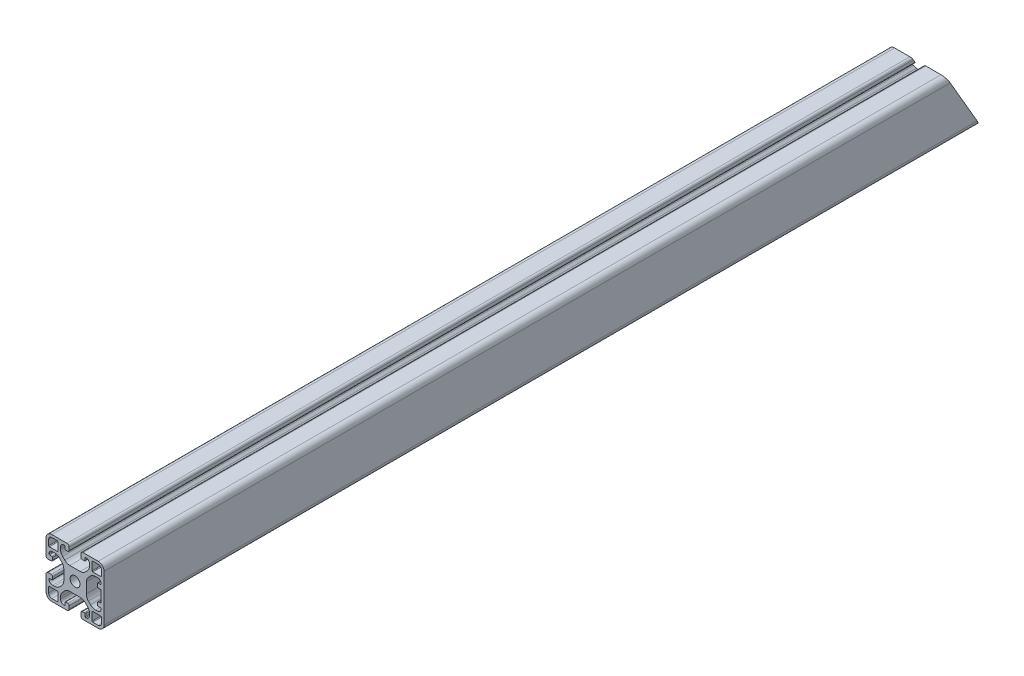
SolidWorks part; units mm, degrees
ref_plane "Piano frontale" through (0, 0, 0) normal (0, 0, 1) x (1, 0, 0)
ref_plane "Piano superiore" through (0, 0, 0) normal (0, 1, 0) x (1, 0, 0)
ref_plane "Piano destro" through (0, 0, 0) normal (1, 0, 0) x (0, 0, -1)
ref_plane "Piano1" through (0, 0, -340) normal (0, 0, -1) x (-1, 0, 0)
sketch "Schizzo1" plane through (0, 0, -340) normal (0, 0, -1) x (-1, 0, 0)
  line L0 (-12.3, -18.2) -> (-16, -18.2)
  line L1 (-18.2, -16) -> (-18.2, -12.3)
  line L2 (-17.7, -11.8) -> (-12.3, -11.8)
  line L3 (-11.8, -12.3) -> (-11.8, -17.7)
  line L4 (-11.8, 17.7) -> (-11.8, 12.3)
  line L5 (-12.3, 11.8) -> (-17.7, 11.8)
  line L6 (-18.2, 12.3) -> (-18.2, 16)
  line L7 (-16, 18.2) -> (-12.3, 18.2)
  line L8 (18.2, 16) -> (18.2, 12.3)
  line L9 (17.7, 11.8) -> (12.3, 11.8)
  line L10 (11.8, 12.3) -> (11.8, 17.7)
  line L11 (12.3, 18.2) -> (16, 18.2)
  line L12 (6.5, -15.5) -> (5, -15.5)
  line L13 (4, -16.5) -> (4, -18.5)
  line L14 (5.5, -20) -> (16, -20)
  line L15 (20, -16) -> (20, -5.5)
  line L16 (18.5, -4) -> (16.5, -4)
  line L17 (15.5, -5) -> (15.5, -6.5)
  line L18 (16, -7) -> (17.55, -7)
  line L19 (18, -7.45) -> (18, -7.5)
  line L20 (15.5, -10) -> (14.1924, -10)
  line L21 (10.6569, -8.5355) -> (9.2145, -7.0931)
  line L22 (7.75, -3.5576) -> (7.75, 3.5576)
  line L23 (9.2145, 7.0931) -> (10.6569, 8.5355)
  line L24 (14.1924, 10) -> (15.5, 10)
  line L25 (18, 7.5) -> (18, 7.45)
  line L26 (17.55, 7) -> (16, 7)
  line L27 (15.5, 6.5) -> (15.5, 5)
  line L28 (16.5, 4) -> (18.5, 4)
  line L29 (20, 5.5) -> (20, 16)
  line L30 (16, 20) -> (5.5, 20)
  line L31 (4, 18.5) -> (4, 16.5)
  line L32 (5, 15.5) -> (6.5, 15.5)
  line L33 (7, 16) -> (7, 17.55)
  line L34 (7.45, 18) -> (7.5, 18)
  line L35 (10, 15.5) -> (10, 14.1924)
  line L36 (8.5355, 10.6569) -> (7.0931, 9.2145)
  line L37 (3.5576, 7.75) -> (-3.5576, 7.75)
  line L38 (-7.0931, 9.2145) -> (-8.5355, 10.6569)
  line L39 (-10, 14.1924) -> (-10, 15.5)
  line L40 (-7.5, 18) -> (-7.45, 18)
  line L41 (-7, 17.55) -> (-7, 16)
  line L42 (-6.5, 15.5) -> (-5, 15.5)
  line L43 (-4, 16.5) -> (-4, 18.5)
  line L44 (-5.5, 20) -> (-16, 20)
  line L45 (-20, 16) -> (-20, -16)
  line L46 (-16, -20) -> (-5.5, -20)
  line L47 (-4, -18.5) -> (-4, -16.5)
  line L48 (-5, -15.5) -> (-6.5, -15.5)
  line L49 (-7, -16) -> (-7, -17.55)
  line L50 (-7.45, -18) -> (-7.5, -18)
  line L51 (-10, -15.5) -> (-10, -14.1924)
  line L52 (-8.5355, -10.6569) -> (-7.0931, -9.2145)
  line L53 (-3.5576, -7.75) -> (3.5576, -7.75)
  line L54 (7.0931, -9.2145) -> (8.5355, -10.6569)
  line L55 (10, -14.1924) -> (10, -15.5)
  line L56 (7.5, -18) -> (7.45, -18)
  line L57 (7, -17.55) -> (7, -16)
  line L58 (18.2, -12.3) -> (18.2, -16)
  line L59 (16, -18.2) -> (12.3, -18.2)
  line L60 (11.8, -17.7) -> (11.8, -12.3)
  line L61 (12.3, -11.8) -> (17.7, -11.8)
  line L62 (-16, 7) -> (-17.5, 7)
  line L63 (-15.5, 10) -> (-14.1924, 10)
  line L64 (-10.6569, 8.5355) -> (-9.2145, 7.0931)
  line L65 (-7.75, 3.5576) -> (-7.75, -3.5576)
  line L66 (-9.2145, -7.0931) -> (-10.6569, -8.5355)
  line L67 (-14.1924, -10) -> (-15.5, -10)
  line L68 (-17.5, -7) -> (-16, -7)
  line L69 (-15.5, -6.5) -> (-15.5, -5)
  line L70 (-16.5, -4) -> (-17.5, -4)
  line L71 (-18, -3.5) -> (-18, 3.5)
  line L72 (-17.5, 4) -> (-16.5, 4)
  line L73 (-15.5, 5) -> (-15.5, 6.5)
  arc A0 (-16, -18.2) -> (-18.2, -16) centre (-16, -16) cw
  arc A1 (-18.2, -12.3) -> (-17.7, -11.8) centre (-17.7, -12.3) cw
  arc A2 (-12.3, -11.8) -> (-11.8, -12.3) centre (-12.3, -12.3) cw
  arc A3 (-11.8, -17.7) -> (-12.3, -18.2) centre (-12.3, -17.7) cw
  arc A4 (-12.3, 18.2) -> (-11.8, 17.7) centre (-12.3, 17.7) cw
  arc A5 (-11.8, 12.3) -> (-12.3, 11.8) centre (-12.3, 12.3) cw
  arc A6 (-17.7, 11.8) -> (-18.2, 12.3) centre (-17.7, 12.3) cw
  arc A7 (-18.2, 16) -> (-16, 18.2) centre (-16, 16) cw
  arc A8 (16, 18.2) -> (18.2, 16) centre (16, 16) cw
  arc A9 (18.2, 12.3) -> (17.7, 11.8) centre (17.7, 12.3) cw
  arc A10 (12.3, 11.8) -> (11.8, 12.3) centre (12.3, 12.3) cw
  arc A11 (11.8, 17.7) -> (12.3, 18.2) centre (12.3, 17.7) cw
  arc A12 (5, -15.5) -> (4, -16.5) centre (5, -16.5) ccw
  arc A13 (4, -18.5) -> (5.5, -20) centre (5.5, -18.5) ccw
  arc A14 (16, -20) -> (20, -16) centre (16, -16) ccw
  arc A15 (20, -5.5) -> (18.5, -4) centre (18.5, -5.5) ccw
  arc A16 (16.5, -4) -> (15.5, -5) centre (16.5, -5) ccw
  arc A17 (15.5, -6.5) -> (16, -7) centre (16, -6.5) ccw
  arc A18 (17.55, -7) -> (18, -7.45) centre (17.55, -7.45) cw
  arc A19 (18, -7.5) -> (15.5, -10) centre (15.5, -7.5) cw
  arc A20 (14.1924, -10) -> (10.6569, -8.5355) centre (14.1924, -5) cw
  arc A21 (9.2145, -7.0931) -> (7.75, -3.5576) centre (12.75, -3.5576) cw
  arc A22 (7.75, 3.5576) -> (9.2145, 7.0931) centre (12.75, 3.5576) cw
  arc A23 (10.6569, 8.5355) -> (14.1924, 10) centre (14.1924, 5) cw
  arc A24 (15.5, 10) -> (18, 7.5) centre (15.5, 7.5) cw
  arc A25 (18, 7.45) -> (17.55, 7) centre (17.55, 7.45) cw
  arc A26 (16, 7) -> (15.5, 6.5) centre (16, 6.5) ccw
  arc A27 (15.5, 5) -> (16.5, 4) centre (16.5, 5) ccw
  arc A28 (18.5, 4) -> (20, 5.5) centre (18.5, 5.5) ccw
  arc A29 (20, 16) -> (16, 20) centre (16, 16) ccw
  arc A30 (5.5, 20) -> (4, 18.5) centre (5.5, 18.5) ccw
  arc A31 (4, 16.5) -> (5, 15.5) centre (5, 16.5) ccw
  arc A32 (6.5, 15.5) -> (7, 16) centre (6.5, 16) ccw
  arc A33 (7, 17.55) -> (7.45, 18) centre (7.45, 17.55) cw
  arc A34 (7.5, 18) -> (10, 15.5) centre (7.5, 15.5) cw
  arc A35 (10, 14.1924) -> (8.5355, 10.6569) centre (5, 14.1924) cw
  arc A36 (7.0931, 9.2145) -> (3.5576, 7.75) centre (3.5576, 12.75) cw
  arc A37 (-3.5576, 7.75) -> (-7.0931, 9.2145) centre (-3.5576, 12.75) cw
  arc A38 (-8.5355, 10.6569) -> (-10, 14.1924) centre (-5, 14.1924) cw
  arc A39 (-10, 15.5) -> (-7.5, 18) centre (-7.5, 15.5) cw
  arc A40 (-7.45, 18) -> (-7, 17.55) centre (-7.45, 17.55) cw
  arc A41 (-7, 16) -> (-6.5, 15.5) centre (-6.5, 16) ccw
  arc A42 (-5, 15.5) -> (-4, 16.5) centre (-5, 16.5) ccw
  arc A43 (-4, 18.5) -> (-5.5, 20) centre (-5.5, 18.5) ccw
  arc A44 (-16, 20) -> (-20, 16) centre (-16, 16) ccw
  arc A45 (-20, -16) -> (-16, -20) centre (-16, -16) ccw
  arc A46 (-5.5, -20) -> (-4, -18.5) centre (-5.5, -18.5) ccw
  arc A47 (-4, -16.5) -> (-5, -15.5) centre (-5, -16.5) ccw
  arc A48 (-6.5, -15.5) -> (-7, -16) centre (-6.5, -16) ccw
  arc A49 (-7, -17.55) -> (-7.45, -18) centre (-7.45, -17.55) cw
  arc A50 (-7.5, -18) -> (-10, -15.5) centre (-7.5, -15.5) cw
  arc A51 (-10, -14.1924) -> (-8.5355, -10.6569) centre (-5, -14.1924) cw
  arc A52 (-7.0931, -9.2145) -> (-3.5576, -7.75) centre (-3.5576, -12.75) cw
  arc A53 (3.5576, -7.75) -> (7.0931, -9.2145) centre (3.5576, -12.75) cw
  arc A54 (8.5355, -10.6569) -> (10, -14.1924) centre (5, -14.1924) cw
  arc A55 (10, -15.5) -> (7.5, -18) centre (7.5, -15.5) cw
  arc A56 (7.45, -18) -> (7, -17.55) centre (7.45, -17.55) cw
  arc A57 (7, -16) -> (6.5, -15.5) centre (6.5, -16) ccw
  arc A58 (17.7, -11.8) -> (18.2, -12.3) centre (17.7, -12.3) cw
  arc A59 (18.2, -16) -> (16, -18.2) centre (16, -16) cw
  arc A60 (12.3, -18.2) -> (11.8, -17.7) centre (12.3, -17.7) cw
  arc A61 (11.8, -12.3) -> (12.3, -11.8) centre (12.3, -12.3) cw
  circle A62 centre (0, 0) radius 3.4
  arc A63 (-15.5, 6.5) -> (-16, 7) centre (-16, 6.5) ccw
  arc A64 (-17.5, 7) -> (-18, 7.5) centre (-17.5, 7.5) cw
  arc A65 (-18, 7.5) -> (-15.5, 10) centre (-15.5, 7.5) cw
  arc A66 (-14.1924, 10) -> (-10.6569, 8.5355) centre (-14.1924, 5) cw
  arc A67 (-9.2145, 7.0931) -> (-7.75, 3.5576) centre (-12.75, 3.5576) cw
  arc A68 (-7.75, -3.5576) -> (-9.2145, -7.0931) centre (-12.75, -3.5576) cw
  arc A69 (-10.6569, -8.5355) -> (-14.1924, -10) centre (-14.1924, -5) cw
  arc A70 (-15.5, -10) -> (-18, -7.5) centre (-15.5, -7.5) cw
  arc A71 (-18, -7.5) -> (-17.5, -7) centre (-17.5, -7.5) cw
  arc A72 (-16, -7) -> (-15.5, -6.5) centre (-16, -6.5) ccw
  arc A73 (-15.5, -5) -> (-16.5, -4) centre (-16.5, -5) ccw
  arc A74 (-17.5, -4) -> (-18, -3.5) centre (-17.5, -3.5) cw
  arc A75 (-18, 3.5) -> (-17.5, 4) centre (-17.5, 3.5) cw
  arc A76 (-16.5, 4) -> (-15.5, 5) centre (-16.5, 5) ccw
extrude "Estrusione-Estrusione1" add sketch "Schizzo1" against normal blind 604
sketch "Schizzo2" plane through (20, 0, 0) normal (1, 0, 0) x (0, 0, -1)
  line L0 (340, -20) -> (316.8146, 20)
  line L4 (340, -16) -> (340, 16)
  line L5 (340, 16) -> (-264, 16)
  line L6 (-264, 16) -> (-264, -16)
  line L7 (-264, -16) -> (340, -16)
  line L8 (340, -16) -> (340, 16)
  line L9 (340, 16) -> (-264, 16)
  line L10 (-264, 16) -> (-264, -16)
  line L11 (-264, -16) -> (340, -16)
  line L12 (340, 16) -> (340, 20)
  line L13 (340, 20) -> (-264, 20)
  line L14 (-264, 20) -> (-264, 16)
  line L15 (-264, 16) -> (340, 16)
  line L16 (340, 16) -> (340, 20)
  line L17 (340, 20) -> (-264, 20)
  line L18 (-264, 20) -> (-264, 16)
  line L19 (-264, 16) -> (340, 16)
  line L20 (340, -20) -> (340, -16)
  line L21 (340, -16) -> (-264, -16)
  line L22 (-264, -16) -> (-264, -20)
  line L23 (-264, -20) -> (340, -20)
  line L24 (340, -20) -> (340, -16)
  line L25 (340, -16) -> (-264, -16)
  line L26 (-264, -16) -> (-264, -20)
  line L27 (-264, -20) -> (340, -20)
  line M13 (340, -16) -> (340, 16)
  line M14 (340, 16) -> (-264, 16)
  line M16 (-264, -16) -> (340, -16)
  dimension "D1" = 0
  dimension "D2" = 0
  dimension "D3" = 0
extrude "Taglio-Estrusione1" cut sketch "Schizzo2" against normal through all contours L0 M16 M13 M14 | L16 L17 L0 M14 | L0 L24 M16
